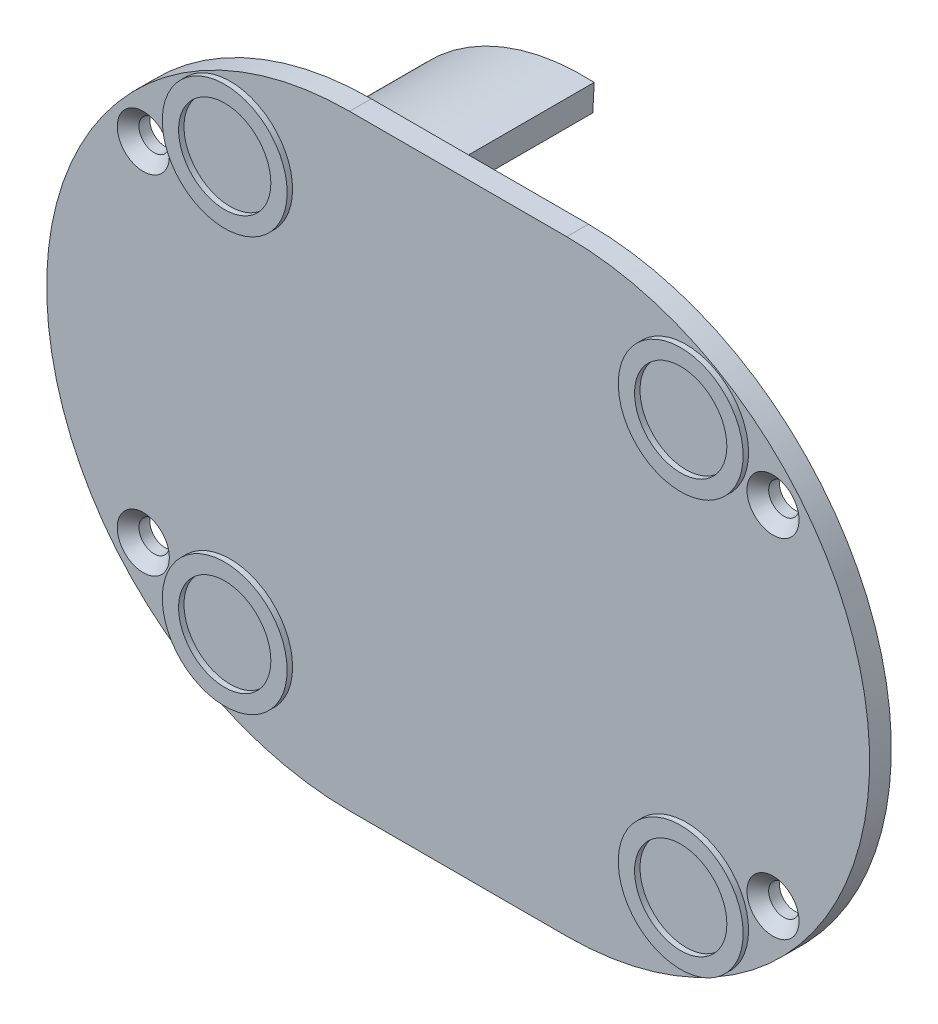
SolidWorks part; units mm, degrees
ref_plane "前视基准面" through (0, 0, 0) normal (0, 0, 1) x (1, 0, 0)
ref_plane "上视基准面" through (0, 0, 0) normal (0, 1, 0) x (1, 0, 0)
ref_plane "右视基准面" through (0, 0, 0) normal (1, 0, 0) x (0, 0, -1)
sketch "草图1" plane through (0, 0, 0) normal (0, 0, 1) x (1, 0, 0)
  line L0 (-20, -27.9) -> (0, -27.9)
  line L1 (0, 27.9) -> (-20, 27.9)
  line L4 (-20, -28) -> (0, -28) construction
  line L5 (0, 28) -> (-20, 28) construction
  arc A0 (0, -27.9) -> (0, 27.9) centre (0, 0) ccw
  arc A1 (-20, 27.9) -> (-20, -27.9) centre (-20, 0) ccw
  arc A4 (-20, 28) -> (-20, -28) centre (-20, 0) ccw construction
  arc A5 (0, -28) -> (0, 28) centre (0, 0) ccw construction
  dimension "D2" = 0.1
extrude "凸台-拉伸1" add sketch "草图1" along normal blind 2
hole_wizard "打孔尺寸(%根据十字)槽沉头自攻螺钉的类型1" positions "草图2" profile "草图3" countersink size "ST2.2" standard "GB"
sketch "草图2" plane through (0, 0, 2) normal (0, 0, 1) x (1, 0, 0)
  line L0 (-20, 0) -> (0, 0) construction
  line L3 (-39, 16) -> (19, 16)
  line L4 (-39, 16) -> (-39, -16)
  line L5 (-39, -16) -> (19, -16)
  line L6 (19, 16) -> (19, -16)
  line L7 (-10, 0) -> (-10, 17.6437) construction
  point P0 (-39, 16)
  point P2 (-39, -16)
  point P4 (19, 16)
  point P6 (19, -16)
  point P16 (-39, 16)
  point P17 (19, -16)
  point P20 (-39, -16)
  point P21 (19, 16)
  point P86 (-39, 16)
  point P92 (-39, -16)
  point P94 (-60.5281, 2.6758)
  point P96 (-55.7473, 1.4628)
  point P98 (-39, 16)
  dimension "D1" = 32
  dimension "D2" = 58
sketch "草图3" plane through (-39, 16, 2) normal (1, 0, 0) x (0, -1, 0)
  line L0 (0, 0) -> (0, 8.3412)
  line L1 (0, 8.3412) -> (1.4, 7.5)
  line L2 (1.4, 7.5) -> (1.4, 1)
  line L3 (1.4, 1) -> (2.4, 0)
  line L5 (2.4, 0) -> (0, 0)
  line L6 (-1.4, 1) -> (-2.4, 0) construction
  line L10 (0, 8.3412) -> (-1.4, 7.5) construction
  line L11 (0, -6.35) -> (0, 107.95) construction
  dimension "孔直径" = 2.8
  dimension "孔深度" = 7.5
  dimension "近端锥形沉头孔直径" = 4.8
  dimension "近端锥形沉头孔角度" = 90
  dimension "导头角度" = 118
sketch "草图4" plane through (0, 0, 2) normal (0, 0, 1) x (1, 0, 0)
  circle A0 centre (11, -19.0526) radius 4.25
  circle A1 centre (11, 19.0526) radius 4.25
  circle A2 centre (-31, 19.0526) radius 4.25
  circle A3 centre (-31, -19.0526) radius 4.25
  dimension "D1" = 8.5
extrude "拉伸-薄壁1" add sketch "草图4" along normal blind 0.5 thin
sketch "草图5" plane through (0, 0, 2) normal (0, 0, 1) x (1, 0, 0)
  arc A0 (-38.9338, 6.4428) -> (-18.9692, 19.9734) centre (-20, 0) cw
  point P4 (-18.96, 20.1508)
  dimension "D1" = 20
extrude "拉伸-薄壁2" add sketch "草图5" against normal blind 21.5 thin
chamfer "倒角1" distance 2 angle 45 2 edges at (-29.8179, 14.4865, 0) (-31.2205, 16.556, 0)
